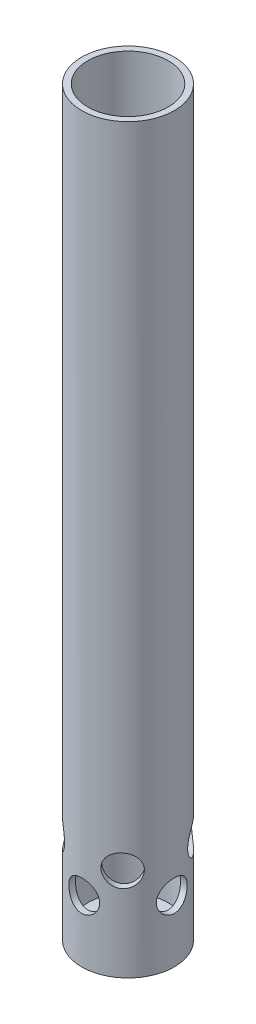
SolidWorks part; units mm, degrees
ref_plane "Front" through (0, 0, 0) normal (0, 0, 1) x (1, 0, 0)
ref_plane "Top" through (0, 0, 0) normal (0, 1, 0) x (1, 0, 0)
ref_plane "Right" through (0, 0, 0) normal (1, 0, 0) x (0, 0, -1)
sketch "Sketch1" plane through (0, 0, 0) normal (0, 1, 0) x (1, 0, 0)
  circle A0 centre (0, 0) radius 9.525
  dimension "D1" = 19.05
extrude "Boss-Extrude1" add sketch "Sketch1" against normal blind 152.4
sketch "Sketch9" plane through (0, 0, 0) normal (0, 1, 0) x (1, 0, 0)
  circle A0 centre (0, 0) radius 8.255
  circle A1 centre (0, 0) radius 9.525 construction
  dimension "D1" = 1.27
extrude "Cut-Extrude5" cut sketch "Sketch9" against normal blind 149.86
ref_plane "Plane1" through (0, -139.7, 0) normal (0, 1, 0) x (1, 0, 0)
sketch "Sketch4" plane through (0, -139.7, 0) normal (0, 1, 0) x (1, 0, 0)
  line L0 (0, 0) -> (0, -9.525) construction
  circle A0 centre (0, 0) radius 9.525 construction
  dimension "D1" = 19.05
ref_plane "Plane2" through (0, -139.7, 9.525) normal (0, 0, 1) x (1, 0, 0)
sketch "Sketch5" plane through (0, -139.7, 9.525) normal (0, 0, 1) x (1, 0, 0)
  line L0 (9.525, 0) -> (-9.525, 0) construction
  circle A0 centre (0, 0) radius 3.175
  dimension "D1" = 6.35
extrude "Cut-Extrude3" cut sketch "Sketch5" against normal blind 3.81
ref_plane "Plane3" through (0, -133.35, 0) normal (0, 1, 0) x (1, 0, 0)
sketch "Sketch6" plane through (0, -133.35, 0) normal (0, 1, 0) x (1, 0, 0)
  line L0 (0, 0) -> (6.1226, -7.2966) construction
  line L1 (0, 0) -> (0, -9.525) construction
  circle A0 centre (0, 0) radius 9.525 construction
  dimension "D1" = 19.05
  dimension "D2" = 40
ref_plane "Plane4" through (6.1226, -133.35, 7.2966) normal (0.6428, 0, 0.766) x (0.766, 0, -0.6428)
sketch "Sketch7" plane through (6.1226, -133.35, 7.2966) normal (0.6428, 0, 0.766) x (0.766, 0, -0.6428)
  line L0 (9.525, 0) -> (-9.525, 0) construction
  circle A0 centre (0, 0) radius 3.175
  dimension "D1" = 6.35
extrude "Cut-Extrude4" cut sketch "Sketch7" against normal blind 3.81
pattern_circular "CirPattern1" count 4 over 360 about axis through (0, -152.4, 0) along (0, 1, 0) of "Cut-Extrude4", "Cut-Extrude3"
sketch "Sketch8" plane through (0, 0, 0) normal (0, 0, 1) x (1, 0, 0)
  line L0 (0, 0) -> (0, -152.4) construction
  line L1 (-9.525, -152.4) -> (9.525, -152.4) construction
